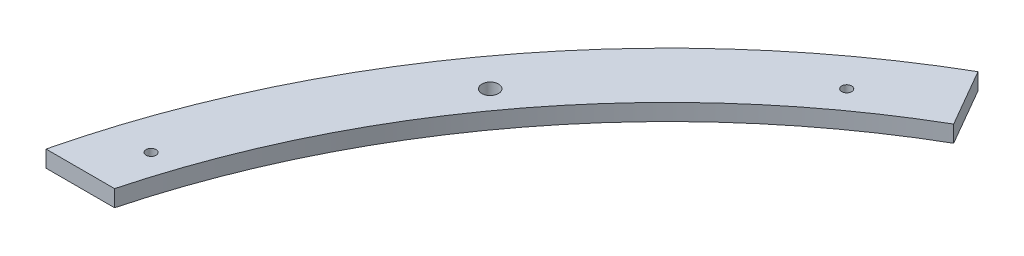
SolidWorks part; units mm, degrees
ref_plane "Front Plane" through (0, 0, 0) normal (0, 0, 1) x (1, 0, 0)
ref_plane "Top Plane" through (0, 0, 0) normal (0, 1, 0) x (1, 0, 0)
ref_plane "Right Plane" through (0, 0, 0) normal (1, 0, 0) x (0, 0, -1)
sketch "Sketch1" plane through (0, 0, 0) normal (0, 1, 0) x (1, 0, 0)
  circle A0 centre (0, 0) radius 254.5
  circle A1 centre (0, 0) radius 234.5
extrude "Boss-Extrude1" add sketch "Sketch1" along normal blind 5
sketch "Sketch2" plane through (0, 5, 0) normal (0, 1, 0) x (1, 0, 0)
  line L0 (-254.5, 0) -> (-226.6942, 0)
  line L1 (-226.6942, 0) -> (-226.6942, 60)
  line L2 (-226.6942, 60) -> (-254.5, 60)
  line L3 (-254.5, 60) -> (-254.5, 0)
  circle A0 centre (0, 0) radius 254.5 construction
  circle A1 centre (0, 0) radius 234.5 construction
  dimension "D1" = 60
extrude "Cut-Extrude1" cut sketch "Sketch2" against normal blind 5
mirror "Mirror1" about plane through (0, 0, 0) normal (0, 0, 1) of "Cut-Extrude1"
sketch "Sketch3" plane through (0, 5, 0) normal (0, 1, 0) x (1, 0, 0)
  circle A0 centre (242.5, 0) radius 2.5
  circle A1 centre (196.1866, -142.5379) radius 2.5
  circle A2 centre (74.9366, -230.6312) radius 2.5
  circle A3 centre (-74.9366, -230.6312) radius 2.5
  circle A4 centre (-196.1866, -142.5379) radius 2.5
  circle A5 centre (-242.5, 0) radius 2.5
  circle A6 centre (-196.1866, 142.5379) radius 2.5
  circle A7 centre (-74.9366, 230.6312) radius 2.5
  circle A8 centre (74.9366, 230.6312) radius 2.5
  circle A9 centre (196.1866, 142.5379) radius 2.5
  point P23 (0, 0)
  dimension "D1" = 242.5
  dimension "D2" = 10
extrude "Cut-Extrude2" cut sketch "Sketch3" against normal blind 5
sketch "Sketch4" plane through (0, 5, 0) normal (0, 1, 0) x (1, 0, 0)
  arc A0 (196.1866, 142.5379) -> (242.5, 0) centre (0, 0) cw
  circle A1 centre (230.6312, 74.9366) radius 1.5
  circle A2 centre (230.6312, -74.9366) radius 1.5
  circle A3 centre (142.5379, -196.1866) radius 1.5
  circle A4 centre (0, -242.5) radius 1.5
  circle A5 centre (-142.5379, -196.1866) radius 1.5
  circle A6 centre (-230.6312, -74.9366) radius 1.5
  circle A7 centre (-230.6312, 74.9366) radius 1.5
  circle A8 centre (-142.5379, 196.1866) radius 1.5
  circle A9 centre (0, 242.5) radius 1.5
  circle A10 centre (142.5379, 196.1866) radius 1.5
  circle A11 centre (230.6312, -74.9366) radius 1.5
  circle A12 centre (142.5379, -196.1866) radius 1.5
  circle A13 centre (0, -242.5) radius 1.5
  circle A14 centre (-142.5379, -196.1866) radius 1.5
  circle A15 centre (-230.6312, -74.9366) radius 1.5
  circle A16 centre (-230.6312, 74.9366) radius 1.5
  circle A17 centre (-142.5379, 196.1866) radius 1.5
  circle A18 centre (0, 242.5) radius 1.5
  circle A19 centre (142.5379, 196.1866) radius 1.5
  point P28 (0, 0)
  point P47 (0, 0)
  dimension "D1" = 10
  dimension "D2" = 10
extrude "Cut-Extrude3" cut sketch "Sketch4" against normal blind 5 contours A4 | A5 | A6 | A7 | A8 | A9 | A10 | A1 | A2 | A3
sketch "Sketch5" plane through (0, 5, 0) normal (0, 1, 0) x (1, 0, 0)
  line L1 (254.5, 0) -> (-396.7126, 0)
  line L2 (254.5, 0) -> (254.5, -357.2264)
  line L3 (254.5, -357.2264) -> (-396.7126, -357.2264)
  line L4 (-396.7126, 0) -> (-396.7126, -357.2264)
  arc A0 (-247.3262, -60) -> (-247.3262, 60) centre (0, 0) ccw construction
extrude "Cut-Extrude4" cut sketch "Sketch5" against normal blind 10
sketch "Sketch6" plane through (0, 5, 0) normal (0, 1, 0) x (1, 0, 0)
  line L0 (254.5, 0) -> (0, 0)
  line L1 (0, 0) -> (-127.25, 220.4035)
  arc A0 (-127.25, 220.4035) -> (254.5, 0) centre (0, 0) cw
  arc A1 (254.5, 0) -> (-247.3262, 60) centre (0, 0) ccw construction
  dimension "D1" = 120
extrude "Cut-Extrude5" cut sketch "Sketch6" against normal blind 10
